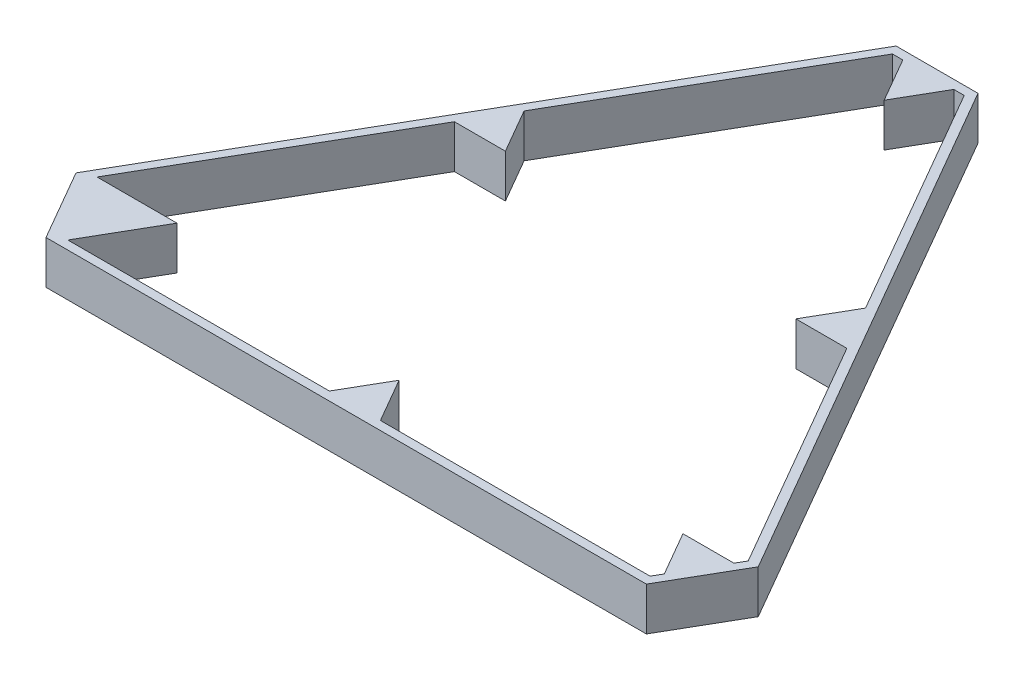
SolidWorks part; units mm, degrees
ref_plane "Front Plane" through (0, 0, 0) normal (0, 0, 1) x (1, 0, 0)
ref_plane "Top Plane" through (0, 0, 0) normal (0, 1, 0) x (1, 0, 0)
ref_plane "Right Plane" through (0, 0, 0) normal (1, 0, 0) x (0, 0, -1)
sketch "Sketch1" plane through (0, 0, 0) normal (0, 1, 0) x (1, 0, 0)
  line L66 (-11.7321, 167.8653) -> (11.7321, 167.8653)
  line L67 (97.7417, 18.8923) -> (86.0096, -1.4282)
  line L68 (97.7417, 18.8923) -> (11.7321, 167.8653)
  line L72 (-97.7417, 18.8923) -> (-86.0096, -1.4282)
  line L73 (-86.0096, -1.4282) -> (86.0096, -1.4282)
  line L74 (-97.7417, 18.8923) -> (-11.7321, 167.8653)
  line L97 (-94.8549, 18.8923) -> (-84.5662, 1.0718)
  line L100 (-94.8549, 18.8923) -> (-74.2776, 18.8923)
  line L106 (-84.5662, 1.0718) -> (-74.2776, 18.8923)
  line L108 (50.0718, 96.4589) -> (55.0718, 87.7987)
  line L109 (41.6077, 85.7987) -> (56.2265, 85.7987)
  line L111 (50.0718, 96.4589) -> (45.0718, 87.7987)
  line L112 (45.0718, 87.7987) -> (55.0718, 87.7987)
  line L115 (56.2265, 85.7987) -> (94.8549, 18.8923)
  line L116 (48.9171, 98.4589) -> (10.2887, 165.3653)
  line L117 (41.6077, 85.7987) -> (48.9171, 98.4589)
  line L118 (-5, 165.3653) -> (5, 165.3653)
  line L121 (-55.0718, 87.7987) -> (-50.0718, 96.4589)
  line L122 (-5, 165.3653) -> (0, 156.7051)
  line L123 (5, 165.3653) -> (0, 156.7051)
  line L125 (0, 152.7051) -> (7.3094, 165.3653)
  line L126 (0, 152.7051) -> (-7.3094, 165.3653)
  line L127 (-10.2887, 165.3653) -> (-7.3094, 165.3653)
  line L128 (7.3094, 165.3653) -> (10.2887, 165.3653)
  line L129 (-50.0718, 96.4589) -> (-45.0718, 87.7987)
  line L130 (-55.0718, 87.7987) -> (-45.0718, 87.7987)
  line L131 (-48.9171, 98.4589) -> (-10.2887, 165.3653)
  line L132 (-41.6077, 85.7987) -> (-48.9171, 98.4589)
  line L133 (-41.6077, 85.7987) -> (-56.2265, 85.7987)
  line L134 (5, 1.0718) -> (-5, 1.0718)
  line L136 (-5, 1.0718) -> (0, 9.7321)
  line L137 (0, 9.7321) -> (5, 1.0718)
  line L139 (0, 13.7321) -> (-7.3094, 1.0718)
  line L143 (84.5662, 1.0718) -> (7.3094, 1.0718)
  line L144 (0, 13.7321) -> (7.3094, 1.0718)
  line L145 (92.2106, 14.3122) -> (87.2106, 5.6519)
  line L147 (87.2106, 5.6519) -> (82.2106, 14.3122)
  line L148 (82.2106, 14.3122) -> (92.2106, 14.3122)
  line L150 (94.8549, 18.8923) -> (93.3653, 16.3122)
  line L151 (78.7465, 16.3122) -> (86.0559, 3.6519)
  line L152 (78.7465, 16.3122) -> (93.3653, 16.3122)
  line L153 (86.0559, 3.6519) -> (84.5662, 1.0718)
  line L154 (-82.2568, 1.0718) -> (-7.3094, 1.0718)
  line L155 (-93.7002, 20.8923) -> (-56.2265, 85.7987)
  line L156 (-70.8135, 20.8923) -> (-93.7002, 20.8923)
  line L159 (-70.8135, 20.8923) -> (-82.2568, 1.0718)
  point P0 (0, 0)
  point P1 (0, 0)
  point P2 (0, 0)
  point P4 (0, 0)
  point P5 (0, 0)
extrude "Boss-Extrude1" add sketch "Sketch1" along normal blind 12.38
